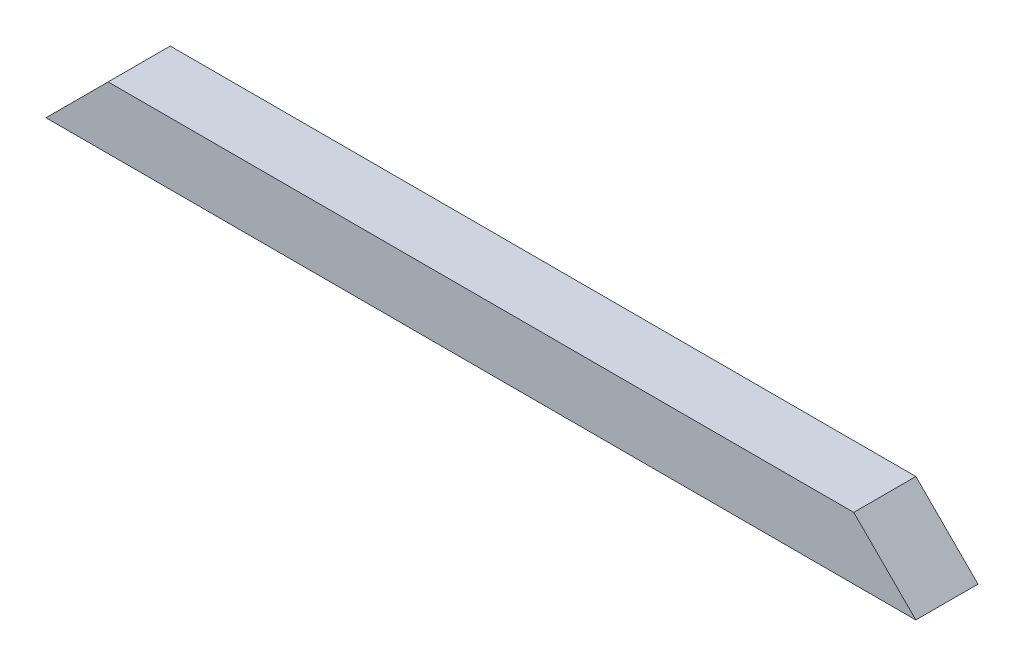
SolidWorks part; units mm, degrees
ref_plane "Alzado" through (0, 0, 0) normal (0, 0, 1) x (1, 0, 0)
ref_plane "Planta" through (0, 0, 0) normal (0, 1, 0) x (1, 0, 0)
ref_plane "Vista lateral" through (0, 0, 0) normal (1, 0, 0) x (0, 0, -1)
sketch "Croquis1" plane through (0, 0, 0) normal (0, 0, 1) x (1, 0, 0)
  line L1 (355.6, -25.4) -> (-355.6, -25.4)
  line L2 (355.6, -25.4) -> (355.6, 25.4)
  line L3 (355.6, 25.4) -> (-355.6, 25.4)
  line L4 (-355.6, -25.4) -> (-355.6, 25.4)
  line L5 (355.6, -25.4) -> (-355.6, 25.4) construction
  line L6 (355.6, 25.4) -> (-355.6, -25.4) construction
  point P0 (0, 0)
  dimension "D1" = 711.2
  dimension "D2" = 50.8
extrude "Saliente-Extruir1" add sketch "Croquis1" along normal blind 50.8
sketch "Croquis2" plane through (0, 0, 50.8) normal (0, 0, 1) x (1, 0, 0)
  line L0 (-355.6, -25.4) -> (355.6, -25.4) construction
  line L1 (-355.6, 25.4) -> (-335.6, 25.4)
  line L2 (-355.6, 25.4) -> (-355.6, -25.4)
  line L3 (-355.6, -25.4) -> (-335.6, -25.4)
  line L4 (-335.6, 25.4) -> (-335.6, -25.4)
  line L5 (-355.6, -25.4) -> (-335.6, 25.4)
  line L6 (0, 0) -> (0, -37.0815) construction
  line L7 (355.6, 25.4) -> (355.6, -25.4)
  line L8 (355.6, -25.4) -> (335.6, 25.4)
  line L9 (355.6, 25.4) -> (335.6, 25.4)
  line M5 (-355.6, 25.4) -> (-355.6, -25.4)
  line M7 (355.6, -25.4) -> (355.6, 25.4)
  line M8 (355.6, 25.4) -> (-355.6, 25.4)
  dimension "D1" = 20
extrude "Cortar-Extruir1" cut sketch "Croquis2" against normal through all contours L8 M7 M8 | L5 M5 M8
sketch "Croquis3" plane through (0, 0, 50.8) normal (0, 0, 1) x (1, 0, 0)
  line L0 (335.6, 25.4) -> (-335.6, 25.4) construction
  line L1 (-355.6, -25.4) -> (-304.8, -25.4)
  line L2 (-355.6, -25.4) -> (-355.6, 25.4)
  line L3 (-355.6, 25.4) -> (-304.8, 25.4)
  line L4 (-304.8, -25.4) -> (-304.8, 25.4)
  line L5 (-304.8, 25.4) -> (-355.6, -25.4)
  line L6 (0, 0) -> (0, 108.5352) construction
  line L7 (355.6, -25.4) -> (355.6, 25.4)
  line L8 (355.6, 25.4) -> (304.8, 25.4)
  line L9 (304.8, 25.4) -> (355.6, -25.4)
  line M5 (-335.6, 25.4) -> (-355.6, -25.4)
  line M7 (355.6, -25.4) -> (335.6, 25.4)
  line M8 (335.6, 25.4) -> (-335.6, 25.4)
  dimension "D1" = 50.8
extrude "Cortar-Extruir2" cut sketch "Croquis3" against normal through all contours L5 M8 M5 | L9 M8 M7
